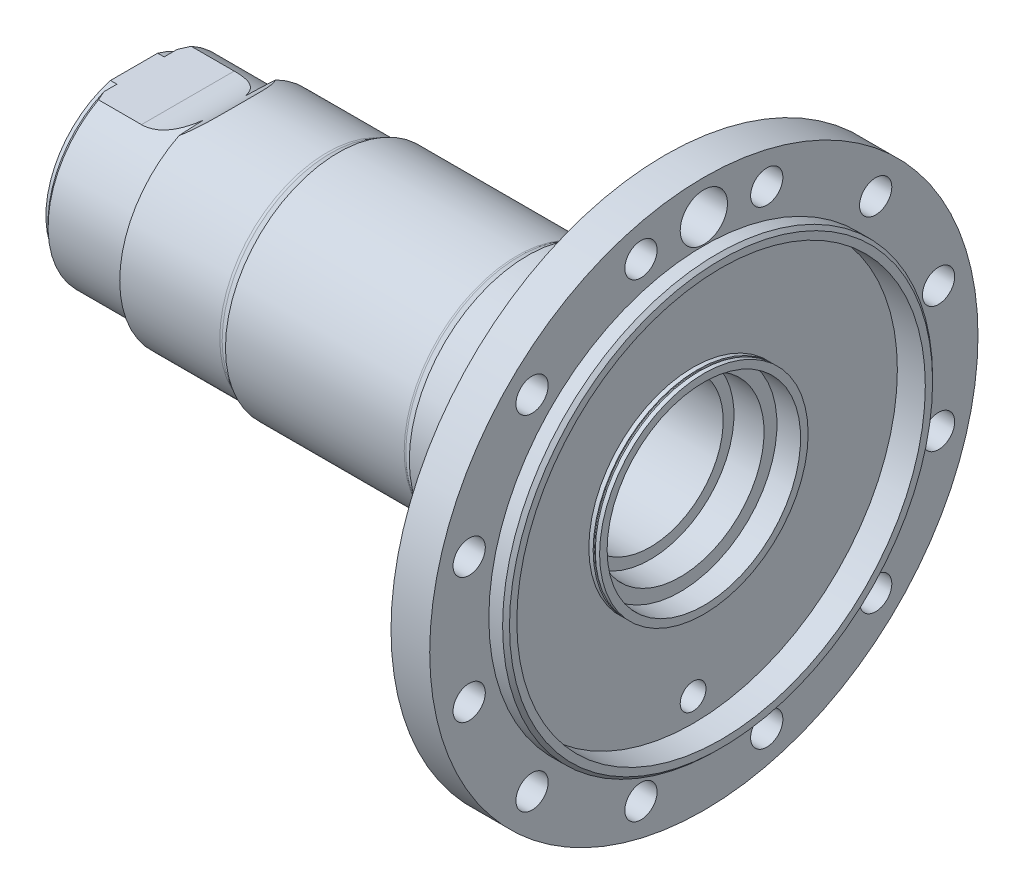
SolidWorks part; units mm, degrees
ref_plane "Спереди" through (0, 0, 0) normal (0, 0, 1) x (1, 0, 0)
ref_plane "Сверху" through (0, 0, 0) normal (0, 1, 0) x (1, 0, 0)
ref_plane "Справа" through (0, 0, 0) normal (1, 0, 0) x (0, 0, -1)
sketch "Эскиз1" plane through (0, 0, 0) normal (0, 0, 1) x (1, 0, 0)
  line L0 (0, 0) -> (273, 0)
  line L1 (0, 0) -> (0, 41)
  line L2 (0, 41) -> (3, 41)
  line L3 (3, 41) -> (3, 43)
  line L4 (3, 43) -> (5, 45)
  line L5 (5, 45) -> (42, 45)
  line L6 (42, 45) -> (43.3397, 50)
  line L7 (43.3397, 50) -> (89.866, 50)
  line L8 (91.366, 50.4019) -> (95, 52.5)
  line L9 (95, 52.5) -> (178.134, 52.5)
  line L10 (179.134, 52.7679) -> (183, 55)
  line L11 (183, 55) -> (213, 55)
  line L12 (215, 57) -> (215, 60.7679)
  line L13 (215, 60.7679) -> (218, 62.5)
  line L14 (218, 62.5) -> (237, 62.5)
  line L15 (239, 64.5) -> (239, 65.5)
  line L16 (239, 65.5) -> (240.4142, 66.9142)
  line L17 (241, 68.3284) -> (241, 78)
  line L18 (241, 78) -> (244.4142, 81.4142)
  line L19 (245, 82.8284) -> (245, 92)
  line L20 (245, 92) -> (246.4142, 93.4142)
  line L21 (247, 94.8284) -> (247, 127.5)
  line L22 (247, 127.5) -> (265, 127.5)
  line L23 (265, 127.5) -> (265, 100)
  line L24 (265, 100) -> (271.4, 100)
  line L25 (271.4, 100) -> (273, 98.4)
  line L26 (273, 98.4) -> (273, 0)
  arc A0 (89.866, 50) -> (91.366, 50.4019) centre (89.866, 53) ccw
  arc A1 (178.134, 52.5) -> (179.134, 52.7679) centre (178.134, 54.5) ccw
  arc A2 (213, 55) -> (215, 57) centre (213, 57) ccw
  arc A3 (237, 62.5) -> (239, 64.5) centre (237, 64.5) ccw
  arc A4 (240.4142, 66.9142) -> (241, 68.3284) centre (239, 68.3284) ccw
  arc A5 (244.4142, 81.4142) -> (245, 82.8284) centre (243, 82.8284) ccw
  arc A6 (246.4142, 93.4142) -> (247, 94.8284) centre (245, 94.8284) ccw
revolve "Повернуть1" add sketch "Эскиз1" angle 360 about L0
sketch "Эскиз2" plane through (0, 0, 0) normal (0, 0, 1) x (1, 0, 0)
  line L0 (0, 0) -> (273, 0)
  line L1 (0, 0) -> (0, 32.7321)
  line L2 (0, 32.7321) -> (3, 31)
  line L3 (3, 31) -> (203.5, 31)
  line L4 (203.5, 31) -> (203.5, 34)
  line L5 (203.5, 34) -> (240, 34)
  line L6 (240, 34) -> (240, 39)
  line L7 (240, 39) -> (254, 39)
  line L8 (254, 39) -> (254, 45)
  line L9 (254, 45) -> (265, 45)
  line L10 (265, 45) -> (265, 95)
  line L11 (265, 95) -> (273, 95)
  line L12 (273, 95) -> (273, 0)
revolve "Вырез-Повернуть1" cut sketch "Эскиз2" angle 360 about L0
sketch "Эскиз3" plane through (0, 0, 0) normal (0, 0, 1) x (1, 0, 0)
  line L0 (0, 0) -> (273, 0) construction
  line L1 (260, 48.5) -> (262, 48.5)
  line L2 (262, 48.5) -> (262, 95)
  line L3 (262, 95) -> (260, 95)
  line L4 (260, 95) -> (260, 48.5)
revolve "Rear_recess_left" cut sketch "Эскиз3" angle 360 about L0
sketch "Эскиз4" plane through (0, 0, 0) normal (0, 0, 1) x (1, 0, 0)
  line L0 (0, 0) -> (273, 0) construction
  line L1 (263, 48) -> (263, 95)
  line L2 (263, 95) -> (262, 95)
  line L3 (262, 95) -> (262, 48)
  arc A0 (262, 48) -> (262.5, 47.5) centre (262.5, 48) ccw
  arc A1 (262.5, 47.5) -> (263, 48) centre (262.5, 48) ccw
revolve "Collar_groove_nominal" cut sketch "Эскиз4" angle 360 about L0
sketch "Эскиз5" plane through (0, 0, 0) normal (0, 0, 1) x (1, 0, 0)
  line L0 (0, 0) -> (273, 0) construction
  line L1 (263, 48.5) -> (265, 48.5)
  line L2 (265, 48.5) -> (265, 95)
  line L3 (265, 95) -> (263, 95)
  line L4 (263, 95) -> (263, 48.5)
revolve "Rear_recess_lip" cut sketch "Эскиз5" angle 360 about L0
sketch "Эскиз6" plane through (0, 0, 0) normal (1, 0, 0) x (0, 0, -1)
  circle A0 centre (109.1496, 29.2466) radius 7.5
extrude "Вырез-Вытянуть1" cut sketch "Эскиз6" along normal through all
sketch "Эскиз7" plane through (0, 0, 0) normal (1, 0, 0) x (0, 0, -1)
  circle A0 centre (79.9031, 79.9031) radius 7.5
extrude "Вырез-Вытянуть2" cut sketch "Эскиз7" along normal through all
sketch "Эскиз8" plane through (0, 0, 0) normal (1, 0, 0) x (0, 0, -1)
  circle A0 centre (29.2466, 109.1496) radius 7.5
extrude "Вырез-Вытянуть3" cut sketch "Эскиз8" along normal through all
sketch "Эскиз9" plane through (0, 0, 0) normal (1, 0, 0) x (0, 0, -1)
  circle A0 centre (-29.2466, 109.1496) radius 7.5
extrude "Вырез-Вытянуть4" cut sketch "Эскиз9" along normal through all
sketch "Эскиз10" plane through (0, 0, 0) normal (1, 0, 0) x (0, 0, -1)
  circle A0 centre (-79.9031, 79.9031) radius 7.5
extrude "Вырез-Вытянуть5" cut sketch "Эскиз10" along normal through all
sketch "Эскиз11" plane through (0, 0, 0) normal (1, 0, 0) x (0, 0, -1)
  circle A0 centre (-109.1496, 29.2466) radius 7.5
extrude "Вырез-Вытянуть6" cut sketch "Эскиз11" along normal through all
sketch "Эскиз12" plane through (0, 0, 0) normal (1, 0, 0) x (0, 0, -1)
  circle A0 centre (-109.1496, -29.2466) radius 7.5
extrude "Вырез-Вытянуть7" cut sketch "Эскиз12" along normal through all
sketch "Эскиз13" plane through (0, 0, 0) normal (1, 0, 0) x (0, 0, -1)
  circle A0 centre (-79.9031, -79.9031) radius 7.5
extrude "Вырез-Вытянуть8" cut sketch "Эскиз13" along normal through all
sketch "Эскиз14" plane through (0, 0, 0) normal (1, 0, 0) x (0, 0, -1)
  circle A0 centre (-29.2466, -109.1496) radius 7.5
extrude "Вырез-Вытянуть9" cut sketch "Эскиз14" along normal through all
sketch "Эскиз15" plane through (0, 0, 0) normal (1, 0, 0) x (0, 0, -1)
  circle A0 centre (29.2466, -109.1496) radius 7.5
extrude "Вырез-Вытянуть10" cut sketch "Эскиз15" along normal through all
sketch "Эскиз16" plane through (0, 0, 0) normal (1, 0, 0) x (0, 0, -1)
  circle A0 centre (79.9031, -79.9031) radius 7.5
extrude "Вырез-Вытянуть11" cut sketch "Эскиз16" along normal through all
sketch "Эскиз17" plane through (0, 0, 0) normal (1, 0, 0) x (0, 0, -1)
  circle A0 centre (109.1496, -29.2466) radius 7.5
extrude "Вырез-Вытянуть12" cut sketch "Эскиз17" along normal through all
sketch "Эскиз18" plane through (0, 0, 0) normal (1, 0, 0) x (0, 0, -1)
  circle A0 centre (0, 111.5) radius 11
extrude "Вырез-Вытянуть13" cut sketch "Эскиз18" along normal through all
sketch "Эскиз19" plane through (0, 0, 0) normal (1, 0, 0) x (0, 0, -1)
  circle A0 centre (0, -84) radius 6
extrude "Вырез-Вытянуть14" cut sketch "Эскиз19" along normal through all
sketch "Эскиз20" plane through (0, 0, 0) normal (0, 0, 1) x (1, 0, 0)
  line L0 (-1, 39.5) -> (25, 39.5)
  line L1 (60, 74.5) -> (60, 150)
  line L2 (60, 150) -> (-1, 150)
  line L3 (-1, 150) -> (-1, 39.5)
  arc A0 (25, 39.5) -> (60, 74.5) centre (25, 74.5) ccw
extrude "Left_flat_84_5_R35" cut sketch "Эскиз20" against normal through all and the other way through all
sketch "Эскиз21" plane through (0, 0, 0) normal (0, 0, 1) x (1, 0, 0)
  line L0 (-1, -25) -> (3, -25)
  line L1 (3, -25) -> (3, -100)
  line L2 (3, -100) -> (-1, -100)
  line L3 (-1, -100) -> (-1, -25)
extrude "Left_end_bottom_20" cut sketch "Эскиз21" against normal through all and the other way through all
